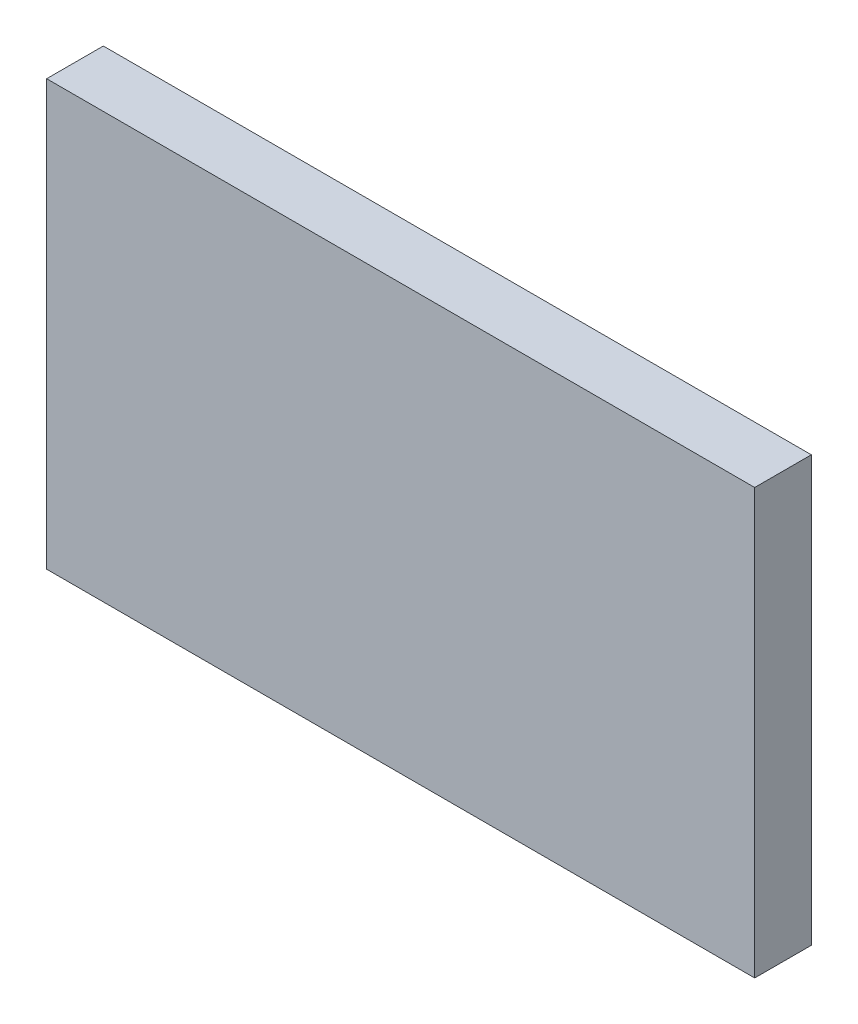
SolidWorks part; units mm, degrees
ref_plane "Plan1" through (0, 0, 0) normal (0, 0, 1) x (1, 0, 0)
ref_plane "Plan2" through (0, 0, 0) normal (0, 1, 0) x (1, 0, 0)
ref_plane "Plan3" through (0, 0, 0) normal (1, 0, 0) x (0, 0, -1)
sketch "Esquisse1" plane through (0, 0, 0) normal (0, 0, 1) x (1, 0, 0)
  line L1 (0, 0) -> (5000, 0)
  line L2 (0, 0) -> (0, 3000)
  line L3 (0, 3000) -> (5000, 3000)
  line L4 (5000, 0) -> (5000, 3000)
extrude "Base-Extrusion" add sketch "Esquisse1" along normal blind 400
